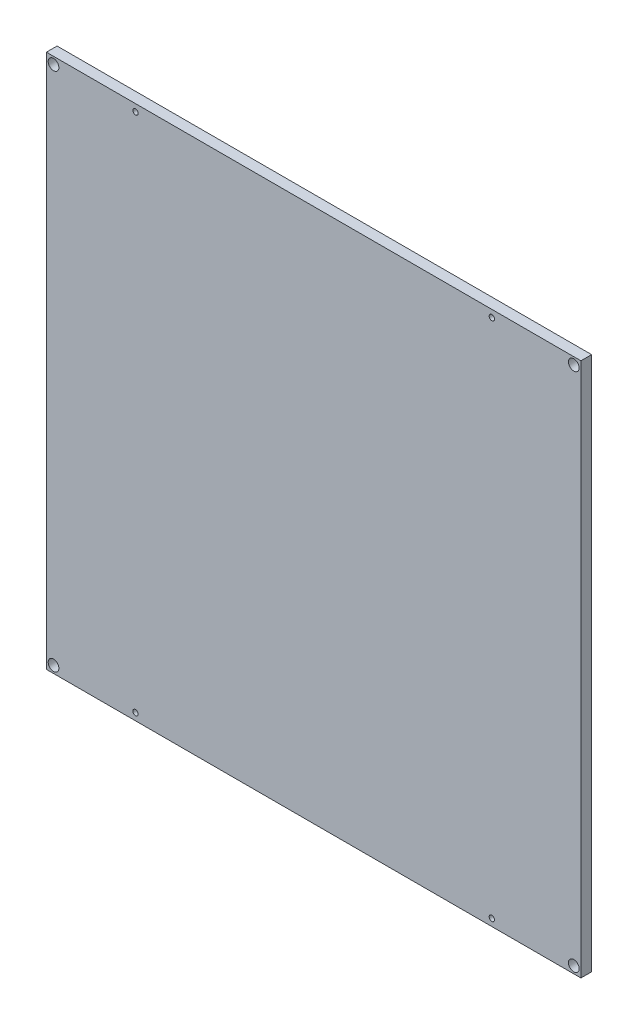
SolidWorks part; units mm, degrees
ref_plane "Front Plane" through (0, 0, 0) normal (0, 0, 1) x (1, 0, 0)
ref_plane "Top Plane" through (0, 0, 0) normal (0, 1, 0) x (1, 0, 0)
ref_plane "Right Plane" through (0, 0, 0) normal (1, 0, 0) x (0, 0, -1)
sketch "Sketch2" plane through (0, 0, 0) normal (0, 0, 1) x (1, 0, 0)
  line L1 (-150, -150) -> (150, -150)
  line L2 (-150, -150) -> (-150, 150)
  line L3 (-150, 150) -> (150, 150)
  line L4 (150, -150) -> (150, 150)
  line L5 (-150, -150) -> (150, 150) construction
  line L6 (-150, 150) -> (150, -150) construction
  point P0 (0, 0)
  dimension "D1" = 300
  dimension "D2" = 300
extrude "Boss-Extrude1" add sketch "Sketch2" along normal blind 6
sketch "Sketch3" plane through (0, 0, 0) normal (0, 0, -1) x (-1, 0, 0)
  circle A0 centre (146, 146) radius 3
  point P0 (146, 146)
  dimension "D1" = 6
extrude "Cut-Extrude1" cut sketch "Sketch3" against normal through all
sketch "Sketch5" plane through (0, 0, 0) normal (0, 0, 1) x (1, 0, 0)
  line L0 (-1146, 146) -> (48854, 146) construction
  line L1 (-150, 150) -> (-150, -150) construction
  circle A0 centre (-100, 146) radius 1.5
  dimension "D1" = 3
  dimension "D2" = 50
extrude "Cut-Extrude2" cut sketch "Sketch5" along normal through all
mirror "Mirror3" about plane through (0, 0, 0) normal (1, 0, 0) of "Cut-Extrude2", "Cut-Extrude1"
mirror "Mirror4" about plane through (0, 0, 0) normal (0, 1, 0) of "Cut-Extrude1", "Cut-Extrude2", "Mirror3"
